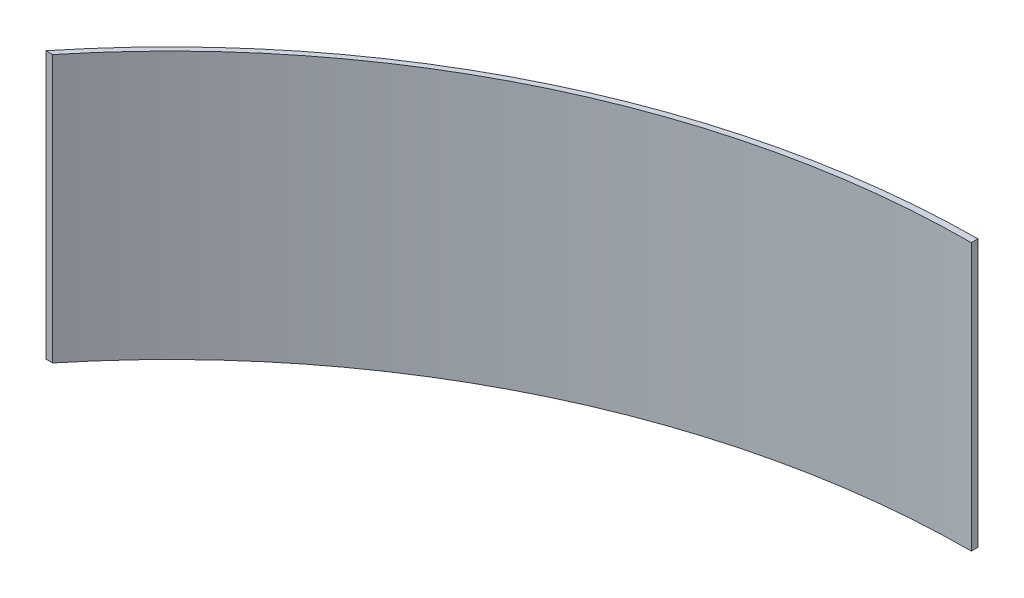
SolidWorks part; units mm, degrees
ref_plane "Front Plane" through (0, 0, 0) normal (0, 0, 1) x (1, 0, 0)
ref_plane "Top Plane" through (0, 0, 0) normal (0, 1, 0) x (1, 0, 0)
ref_plane "Right Plane" through (0, 0, 0) normal (1, 0, 0) x (0, 0, -1)
sketch "Sketch1" plane through (0, 0, 0) normal (0, 0, 1) x (1, 0, 0)
  line L1 (-304.8, -152.4) -> (304.8, -152.4)
  line L2 (-304.8, -152.4) -> (-304.8, 152.4)
  line L3 (-304.8, 152.4) -> (304.8, 152.4)
  line L4 (304.8, -152.4) -> (304.8, 152.4)
  line L5 (0, 152.4) -> (0, -152.4) construction
  line L6 (-304.8, 0) -> (304.8, 0) construction
  point P0 (0, 0)
  point P4 (-190.5, 0)
  point P5 (190.5, 0)
  point P6 (0, 106.68)
  point P7 (0, -106.68)
  dimension "Length" = 609.6
  dimension "Width" = 304.8
  dimension "Break" = 114.3
  dimension "D2" = 114.3
  dimension "D1" = 45.72
  dimension "D3" = 45.72
sketch "Sketch2" plane through (0, 0, 0) normal (1, 0, 0) x (0, 0, -1)
  line L0 (-1.5875, -152.4) -> (1.5875, -152.4)
  dimension "Thickness" = 3.175
sketch "Sketch3" plane through (0, 0, 0) normal (0, 0, 1) x (1, 0, 0)
  line L0 (-304.8, -152.4) -> (-304.8, 152.4) construction
  line L1 (-304.8, -152.4) -> (304.8, -152.4) construction
  line L2 (304.8, -152.4) -> (304.8, 152.4) construction
  line L3 (-304.8, 152.4) -> (304.8, 152.4) construction
  line L4 (-304.8, -152.4) -> (-304.8, 152.4)
  line L5 (-304.8, -152.4) -> (304.8, -152.4)
  line L6 (304.8, -152.4) -> (304.8, 152.4)
  line L7 (-304.8, 152.4) -> (304.8, 152.4)
extrude "Boss-Extrude1" add sketch "Sketch3" along normal mid plane 609.6
sketch "Sketch4" plane through (0, 0, -304.8) normal (0, 0, -1) x (-1, 0, 0)
  line L0 (-304.8, 152.4) -> (304.8, 152.4)
  line L1 (304.8, 152.4) -> (304.8, -152.4)
  line L2 (304.8, -152.4) -> (-304.8, -152.4)
  line L3 (-304.8, -152.4) -> (-304.8, 152.4)
  line L4 (-304.8, 152.4) -> (-304.8, 25.4)
  line L5 (-304.8, 25.4) -> (304.8, 25.4)
  line L6 (304.8, 25.4) -> (304.8, 152.4)
  line M6 (-304.8, -152.4) -> (304.8, -152.4)
  line M7 (304.8, -152.4) -> (304.8, 152.4)
  dimension "D1" = 127
extrude "Cut-Extrude1" cut sketch "Sketch4" against normal blind 609.6 contours L5 L3 M6 M7
sketch "Sketch6" plane through (0, 152.4, 0) normal (0, 1, 0) x (1, 0, 0)
  line L0 (59.8564, 27.6282) -> (59.8564, 30.8032)
  line L1 (-235.9918, -113.2991) -> (-239.1668, -113.2991)
  line L2 (-304.8, 304.8) -> (-304.8, -304.8)
  line L3 (-304.8, -304.8) -> (304.8, -304.8)
  line L4 (304.8, -304.8) -> (304.8, 304.8)
  line L5 (304.8, 304.8) -> (-304.8, 304.8)
  arc A0 (59.8564, 27.6282) -> (-235.9918, -113.2991) centre (59.8564, -353.3718) ccw
  arc A1 (-239.1668, -113.2991) -> (59.8564, 30.8032) centre (61.9223, -355.7827) cw
  dimension "D1" = 3.175
  dimension "D2" = 381
  dimension "D3" = 3.175
  dimension "D4" = 3.175
extrude "Cut-Extrude2" cut sketch "Sketch6" against normal blind 254
equation "\"D1@Boss-Extrude1\"=\"thickness@sketch2\""
equation "\"Break@Sketch1\"=\"Length@Sketch1\" * .1875"
equation "\"D2@Sketch1\" = \"Break@Sketch1\""
equation "\"D1@Sketch1\"=\"Width@Sketch1\"*0.15"
equation "\"D3@Sketch1\"=\"D1@Sketch1\""
